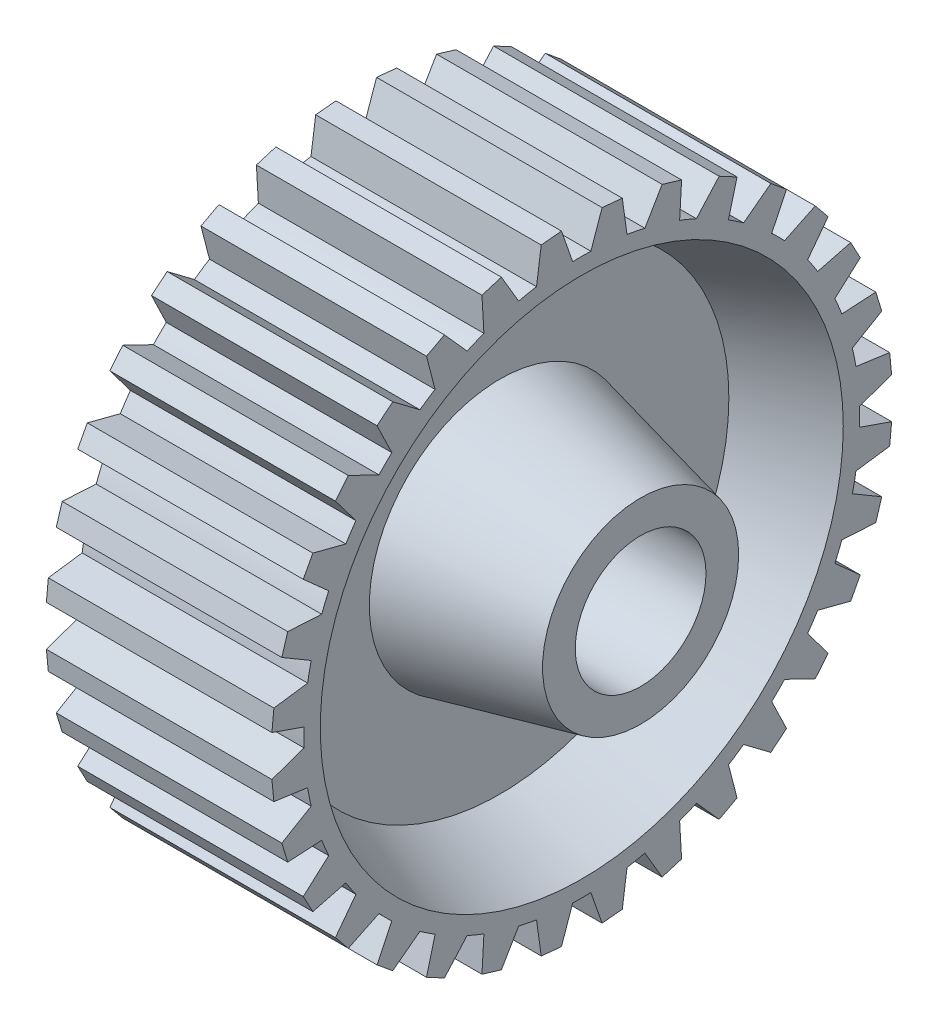
SolidWorks part; units mm, degrees
material "Commercially Pure titanium (Ti-55)  UNS R50550*"
ref_plane "Front Plane" through (0, 0, 0) normal (0, 0, 1) x (1, 0, 0)
ref_plane "Top Plane" through (0, 0, 0) normal (0, 1, 0) x (1, 0, 0)
ref_plane "Right Plane" through (0, 0, 0) normal (1, 0, 0) x (0, 0, -1)
sketch "Sketch1" plane through (0, 0, 0) normal (0, 0, 1) x (1, 0, 0)
  line L0 (0, 9.652) -> (0, 53.975) construction
  line L1 (21.9075, 53.975) -> (-21.9075, 53.975)
  line L2 (-21.9075, 53.975) -> (-21.9075, 50.8)
  line L3 (-21.9075, 50.8) -> (-6.0325, 44.45)
  line L4 (-6.0325, 44.45) -> (-6.0325, 25.4)
  line L5 (-6.0325, 25.4) -> (-33.3375, 19.05)
  line L6 (-33.3375, 19.05) -> (-33.3375, 12.7)
  line L7 (-33.3375, 12.7) -> (-12.7127, 12.7)
  line L8 (-12.7127, 12.7) -> (-12.7127, 9.652)
  line L9 (-12.7127, 9.652) -> (12.7127, 9.652)
  line L10 (0, 0) -> (-12.7127, 0) construction
  line L11 (12.7127, 12.7) -> (12.7127, 9.652)
  line L12 (33.3375, 12.7) -> (12.7127, 12.7)
  line L13 (33.3375, 19.05) -> (33.3375, 12.7)
  line L14 (6.0325, 25.4) -> (33.3375, 19.05)
  line L15 (6.0325, 44.45) -> (6.0325, 25.4)
  line L16 (21.9075, 50.8) -> (6.0325, 44.45)
  line L17 (21.9075, 53.975) -> (21.9075, 50.8)
  dimension "D1" = 20.6248
  dimension "D2" = 33.3375
  dimension "D3" = 11.43
  dimension "D4" = 50.8
  dimension "D5" = 9.652
  dimension "D6" = 12.7
  dimension "D7" = 19.05
  dimension "D8" = 25.4
  dimension "D9" = 44.45
  dimension "D10" = 15.875
  dimension "D11" = 53.975
revolve "Revolve1" add sketch "Sketch1" angle 360 about L10
sketch "Sketch2" plane through (-21.9075, 0, 0) normal (-1, 0, 0) x (0, 0, 1)
  line L0 (0, 0) -> (53.975, 0) construction
  line L1 (60.1958, 3.9454) -> (53.9461, 1.766)
  line L2 (60.1958, 3.9454) -> (59.8089, 7.874)
  line L3 (59.8089, 7.874) -> (53.2541, 8.7923)
  line L4 (53.9461, 1.766) -> (0, 0) construction
  line L5 (60.1958, 3.9454) -> (0, 0) construction
  line L6 (59.8089, 7.874) -> (0, 0) construction
  line L7 (53.2541, 8.7923) -> (0, 0) construction
  circle A0 centre (0, 0) radius 53.975 construction
  arc A1 (53.9461, 1.766) -> (53.2541, 8.7923) centre (0, 0) ccw
  circle A2 centre (0, 0) radius 60.325 construction
  dimension "D1" = 120.65
  dimension "D2" = 1.875
  dimension "D3" = 3.75
  dimension "D4" = 7.5
  dimension "D5" = 9.375
extrude "Boss-Extrude1" add sketch "Sketch2" against normal blind 43.815
pattern_circular "CirPattern1" count 32 over 360 about axis through (0, 0, 0) along (1, 0, 0) of "Boss-Extrude1"
sketch "Sketch3" plane through (-12.7127, 0, 0) normal (-1, 0, 0) x (0, 0, 1)
  line L0 (0, 0) -> (0, 11.8872) construction
  line L1 (0, 11.8872) -> (-2.4384, 11.8872)
  line L2 (-2.4384, 11.8872) -> (-2.4384, 9.3389)
  line L3 (0, 11.8872) -> (2.4384, 11.8872)
  line L4 (2.4384, 11.8872) -> (2.4384, 9.3389)
  circle A0 centre (0, 0) radius 9.652 construction
  arc A1 (2.4384, 9.3389) -> (-2.4384, 9.3389) centre (0, 0) ccw
  point P3 (2.4384, 10.6131)
  dimension "D1" = 4.8768
  dimension "D2" = 2.4384
  dimension "D3" = 11.8872
extrude "Cut-Extrude1" cut sketch "Sketch3" against normal up to next
